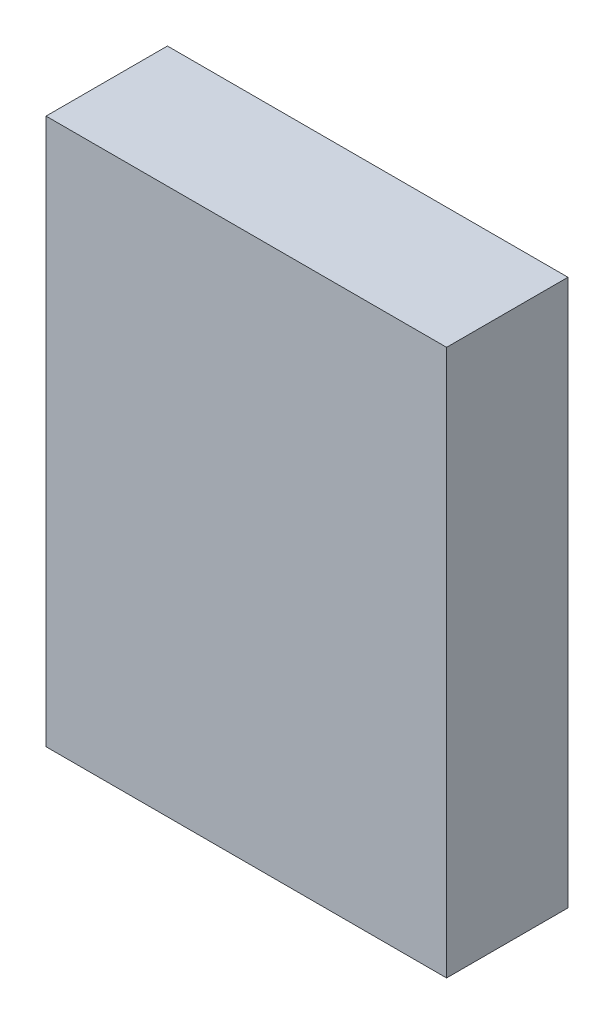
SolidWorks part; units mm, degrees
ref_plane "Płaszczyzna przednia" through (0, 0, 0) normal (0, 0, 1) x (1, 0, 0)
ref_plane "Płaszczyzna górna" through (0, 0, 0) normal (0, 1, 0) x (1, 0, 0)
ref_plane "Płaszczyzna prawa" through (0, 0, 0) normal (1, 0, 0) x (0, 0, -1)
sketch "Sketch1" plane through (0, 0, 0) normal (0, 0, 1) x (1, 0, 0)
  line L1 (-330, -450) -> (330, -450)
  line L2 (-330, -450) -> (-330, 450)
  line L3 (-330, 450) -> (330, 450)
  line L4 (330, -450) -> (330, 450)
  line L5 (-330, -450) -> (330, 450) construction
  line L6 (-330, 450) -> (330, -450) construction
  point P0 (0, 0)
  dimension "D1" = 660
  dimension "D2" = 900
extrude "Boss-Extrude1" add sketch "Sketch1" along normal blind 200
